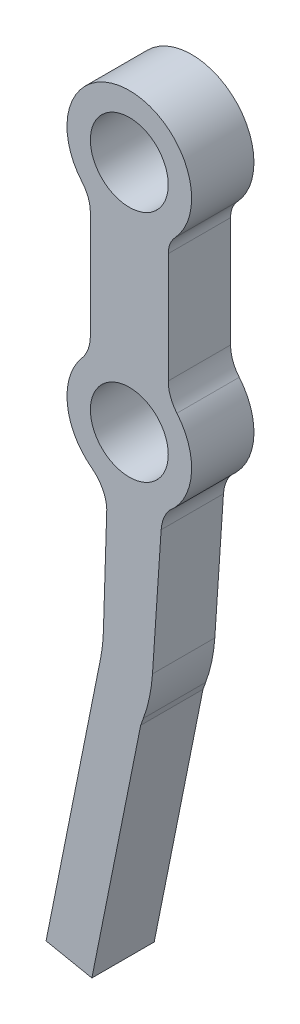
SolidWorks part; units mm, degrees
ref_plane "前视基准面" through (0, 0, 0) normal (0, 0, 1) x (1, 0, 0)
ref_plane "上视基准面" through (0, 0, 0) normal (0, 1, 0) x (1, 0, 0)
ref_plane "右视基准面" through (0, 0, 0) normal (1, 0, 0) x (0, 0, -1)
sketch "草图1" plane through (0, 0, 0) normal (0, 0, 1) x (1, 0, 0)
  line L1 (1.4877, -12.4556) -> (2.0432, -4.1662)
  line L2 (2.5, 4.3346) -> (2.5, 11.4118)
  line L3 (-2.5, 11.1938) -> (-2.5, 4.3379)
  line L4 (-1.4455, -4.7731) -> (-1.6632, -11.6639)
  line L5 (-1.8535, -13.3146) -> (-5.3433, -30.7149)
  line L6 (-5.3433, -30.7149) -> (-2.4019, -31.3048)
  line L7 (-2.4019, -31.3048) -> (0.7289, -15.6948)
  line L8 (0, 15.235) -> (0, 0.235) construction
  line L9 (0.9031, -15.2178) -> (0.7289, -15.6948)
  circle A0 centre (0, 0.235) radius 2.5
  circle A1 centre (0, 15.235) radius 2.5
  arc A2 (2.5455, -2.8505) -> (2.0432, -4.1662) centre (4.4378, -4.3267) ccw
  arc A3 (2.5455, -2.8505) -> (3.0555, 2.8165) centre (0, 0.235) ccw
  arc A4 (2.5, 4.3346) -> (3.0555, 2.8165) centre (4.8523, 4.3346) ccw
  arc A5 (2.9328, 12.515) -> (2.5, 11.4118) centre (4.1224, 11.4118) ccw
  arc A6 (2.9328, 12.515) -> (-3.0313, 12.6252) centre (0, 15.235) ccw
  arc A7 (-2.5, 11.1938) -> (-3.0313, 12.6252) centre (-4.6937, 11.1938) ccw
  arc A8 (-3.0568, 2.8149) -> (-2.5, 4.3379) centre (-4.8613, 4.3379) ccw
  arc A9 (-3.0568, 2.8149) -> (-2.4019, -2.9636) centre (0, 0.235) ccw
  arc A10 (-1.4455, -4.7731) -> (-2.4019, -2.9636) centre (-3.843, -4.8827) ccw
  arc A11 (-1.6632, -11.6639) -> (-1.8535, -13.3146) centre (-11.6583, -11.3481) cw
  arc A14 (1.4877, -12.4556) -> (0.9031, -15.2178) centre (-8.49, -11.7869) cw
  point P32 (0, 0)
  point P33 (0, 0)
  point P34 (-2.4019, -31.3048)
  point P35 (0.9031, -15.2178)
  point P36 (0, 0)
  dimension "D2" = 5
  dimension "D3" = 5
  dimension "D6" = 4
  dimension "D7" = 4
  dimension "D8" = 10
  dimension "D9" = 10
  dimension "D1" = 15
  dimension "D4" = 5
  dimension "D5" = 3
extrude "凸台-拉伸1" add sketch "草图1" along normal blind 4
